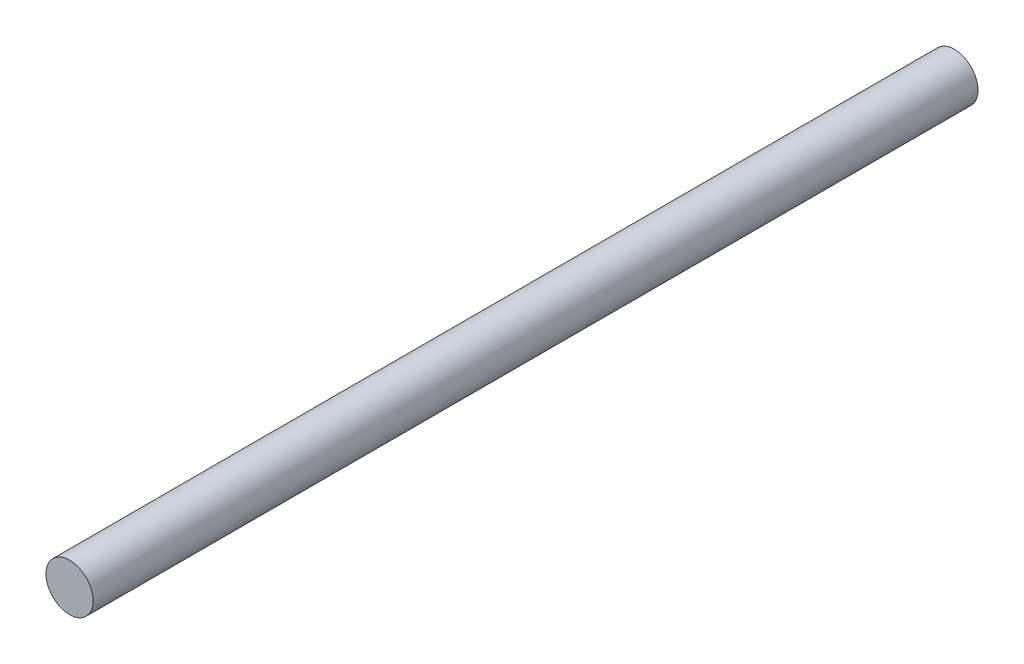
SolidWorks part; units mm, degrees
ref_plane "前视基准面" through (0, 0, 0) normal (0, 0, 1) x (1, 0, 0)
ref_plane "上视基准面" through (0, 0, 0) normal (0, 1, 0) x (1, 0, 0)
ref_plane "右视基准面" through (0, 0, 0) normal (1, 0, 0) x (0, 0, -1)
sketch "草图1" plane through (0, 0, 0) normal (0, 0, 1) x (1, 0, 0)
  circle A0 centre (0, 0) radius 4
  dimension "D1" = 8
extrude "凸台-拉伸1" add sketch "草图1" along normal blind 150
